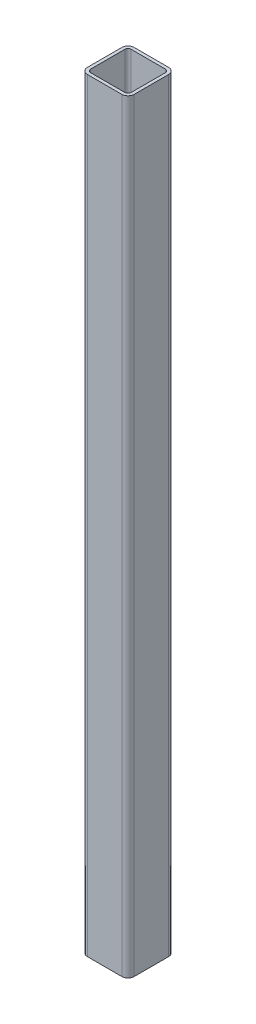
SolidWorks part; units mm, degrees
material "AISI 1010 钢，热轧条材"
ref_plane "前视基准面" through (0, 0, 0) normal (0, 0, 1) x (1, 0, 0)
ref_plane "上视基准面" through (0, 0, 0) normal (0, 1, 0) x (1, 0, 0)
ref_plane "右视基准面" through (0, 0, 0) normal (1, 0, 0) x (0, 0, -1)
sketch "草图1" plane through (0, 0, 0) normal (0, 1, 0) x (1, 0, 0)
  line L0 (4, 2) -> (26, 2)
  line L1 (4, 0) -> (26, 0)
  line L2 (0, 4) -> (0, 26)
  line L3 (4, 30) -> (26, 30)
  line L4 (30, 4) -> (30, 26)
  line L5 (28, 4) -> (28, 26)
  line L6 (4, 28) -> (26, 28)
  line L7 (2, 4) -> (2, 26)
  arc A0 (4, 0) -> (0, 4) centre (4, 4) cw
  arc A1 (26, 0) -> (30, 4) centre (26, 4) ccw
  arc A2 (26, 30) -> (30, 26) centre (26, 26) cw
  arc A3 (0, 26) -> (4, 30) centre (4, 26) cw
  arc A4 (26, 2) -> (28, 4) centre (26, 4) ccw
  arc A5 (26, 28) -> (28, 26) centre (26, 26) cw
  arc A6 (2, 26) -> (4, 28) centre (4, 26) cw
  arc A7 (4, 2) -> (2, 4) centre (4, 4) cw
  point P7 (0, 0)
  point P10 (30, 0)
  point P13 (30, 30)
  point P16 (0, 30)
  dimension "D3" = 4
  dimension "D1" = 30
  dimension "D2" = 30
  dimension "D4" = 2
extrude "凸台-拉伸1" add sketch "草图1" along normal mid plane 490
sketch "草图2" plane through (0, 0, -30) normal (0, 0, 1) x (1, 0, 0)
  line L1 (0, 20) -> (23, 20)
  line L2 (0, 20) -> (0, -20)
  line L3 (0, -20) -> (23, -20)
  line L4 (23, 20) -> (23, -20)
  dimension "D1" = 23
  dimension "D2" = 40
extrude "切除-拉伸1" cut sketch "草图2" along normal blind 18
